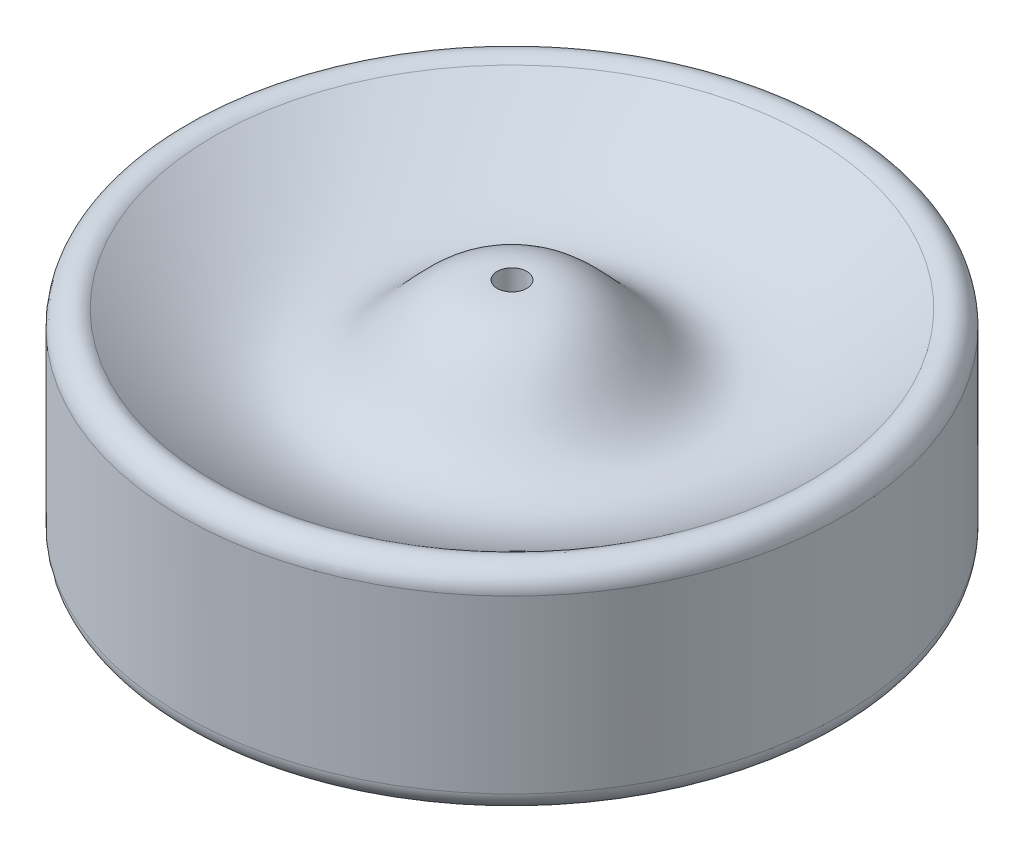
SolidWorks part; units mm, degrees
ref_plane "Front Plane" through (0, 0, 0) normal (0, 0, 1) x (1, 0, 0)
ref_plane "Top Plane" through (0, 0, 0) normal (0, 1, 0) x (1, 0, 0)
ref_plane "Right Plane" through (0, 0, 0) normal (1, 0, 0) x (0, 0, -1)
sketch "Sketch1" plane through (0, 0, 0) normal (0, 0, 1) x (1, 0, 0)
  line L0 (0, 0) -> (50, 0)
  line L1 (50, 0) -> (50, 35)
  line L2 (0, 0) -> (0, 35) construction
  line L3 (0, 0) -> (0, 35)
  spline S0 degree 3 poles (0, 35) (20.1906, 38.0736) (11.6564, 5.0241) (50, 35) knots 0 0 0 0 1 1 1 1
  dimension "D1" = 50
  dimension "D2" = 35
revolve "Revolve1" add sketch "Sketch1" angle 360 about L2
fillet "Fillet1" radius 3 2 edges at (0, 0, -50) (0, 35, -50)
ref_plane "Plane1" through (0, 50, 0) normal (0, 1, 0) x (1, 0, 0)
sketch "Sketch2" plane through (0, 50, 0) normal (0, 1, 0) x (1, 0, 0)
  circle A0 centre (0, 0) radius 2.25
  dimension "D1" = 4.5
extrude "Cut-Extrude1" cut sketch "Sketch2" against normal blind 30
sketch "Sketch3" plane through (0, 0, 0) normal (1, 0, 0) x (0, 0, -1)
  line L5 (2.25, 35.201) -> (-2.25, 35.201) construction
  line L12 (-1.022, 20.4924) -> (36.277, 297.997)
  line L13 (0.261, 20.6545) -> (37.5159, 297.8305)
  line L14 (-2.2776, 20.5349) -> (35.0382, 298.1635)
  line L15 (-2.2167, 20.9875) -> (35.0382, 298.1635) construction
  line L16 (-2.0575, 35.201) -> (-2.2856, 20) construction
  line L17 (2.25, 20) -> (-2.25, 20) construction
  line L18 (36.277, 297.997) -> (36.277, 21.9901) construction
  line L19 (-0.9779, 20.821) -> (36.277, 297.997) construction
  point P0 (9.0545, 35.201)
  dimension "D3" = 280
  dimension "D1" = 1.25
  dimension "D2" = 1.25
